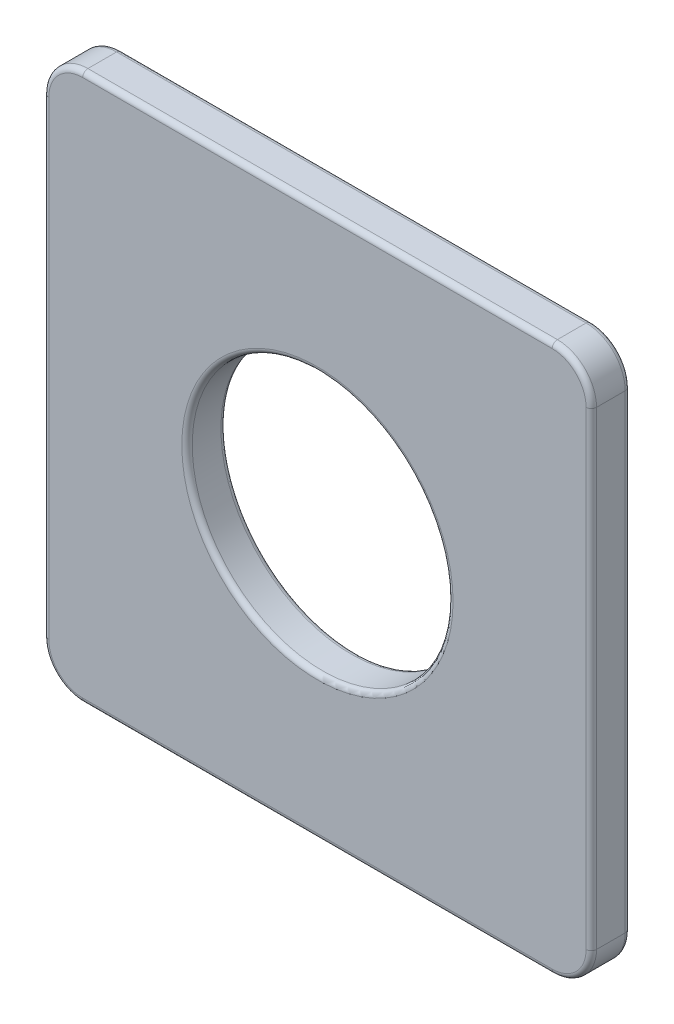
SolidWorks part; units mm, degrees
ref_plane "Front Plane" through (0, 0, 0) normal (0, 0, 1) x (1, 0, 0)
ref_plane "Top Plane" through (0, 0, 0) normal (0, 1, 0) x (1, 0, 0)
ref_plane "Right Plane" through (0, 0, 0) normal (1, 0, 0) x (0, 0, -1)
sketch "Sketch1" plane through (0, 0, 0) normal (0, 0, 1) x (1, 0, 0)
  line L1 (10.5, -10.5) -> (-10.5, -10.5)
  line L2 (10.5, -10.5) -> (10.5, 10.5)
  line L3 (10.5, 10.5) -> (-10.5, 10.5)
  line L4 (-10.5, -10.5) -> (-10.5, 10.5)
  line L5 (10.5, -10.5) -> (-10.5, 10.5) construction
  line L6 (10.5, 10.5) -> (-10.5, -10.5) construction
  point P0 (0, 0)
  dimension "D1" = 21
  dimension "D2" = 21
extrude "Boss-Extrude1" add sketch "Sketch1" along normal mid plane 1.5
fillet "Fillet1" radius 1.5 4 edges at (-10.5, 10.5, 0) (10.5, -10.5, 0) (-10.5, -10.5, 0) (10.5, 10.5, 0)
sketch "Sketch2" plane through (0, 0, -0.75) normal (0, 0, -1) x (-1, 0, 0)
  circle A0 centre (0, 0) radius 5
  dimension "D1" = 10
extrude "Cut-Extrude1" cut sketch "Sketch2" against normal through all
fillet "Fillet2" radius 0.2 18 edges at (10.0607, 10.0607, 0.75) (10.5, 0, 0.75) (10.0607, -10.0607, 0.75) (0, -10.5, 0.75) (-10.0607, -10.0607, 0.75) (-10.5, 0, 0.75) (-10.0607, 10.0607, 0.75) (0, 10.5, 0.75) (-5, 0, 0.75) (-10.0607, -10.0607, -0.75) (0, -10.5, -0.75) (10.0607, -10.0607, -0.75) (10.5, 0, -0.75) (10.0607, 10.0607, -0.75) (0, 10.5, -0.75) (-10.0607, 10.0607, -0.75) (-10.5, 0, -0.75) (-5, 0, -0.75)
